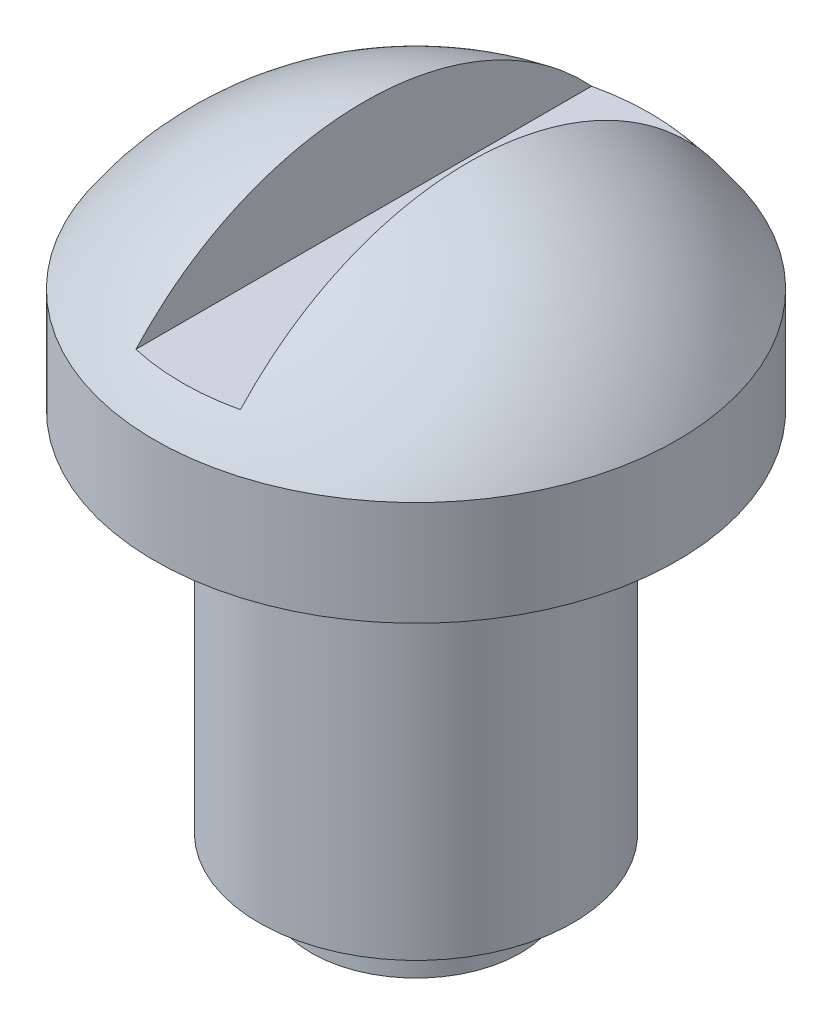
SolidWorks part; units mm, degrees
ref_plane "Front Plane" through (0, 0, 0) normal (0, 0, 1) x (1, 0, 0)
ref_plane "Top Plane" through (0, 0, 0) normal (0, 1, 0) x (1, 0, 0)
ref_plane "Right Plane" through (0, 0, 0) normal (1, 0, 0) x (0, 0, -1)
sketch "Sketch2" plane through (0, 0, 0) normal (0, 0, 1) x (1, 0, 0)
  line L0 (0, 0) -> (0, -12.6834)
  line L1 (0, -12.6834) -> (2, -12.6834)
  line L2 (2, -12.6834) -> (2, -11.6834)
  line L3 (2, -11.6834) -> (3, -11.6834)
  line L4 (3, -11.6834) -> (3, -4.6834)
  line L5 (3, -4.6834) -> (5, -4.6834)
  line L6 (5, -4.6834) -> (5, -2.6834)
  arc A0 (0, 0) -> (5, -2.6834) centre (0, -6) cw
  point P10 (0, 0)
  point P11 (0, 0)
  dimension "D6" = 6
  dimension "D1" = 2
  dimension "D2" = 3
  dimension "D3" = 7
  dimension "D4" = 2
  dimension "D5" = 1
  dimension "D7" = 5
revolve "Revolve1" add sketch "Sketch2" angle 360 about L0
sketch "Sketch3" plane through (0, 0, 0) normal (0, 0, 1) x (1, 0, 0)
  line L1 (-1, 2) -> (1, 2)
  line L2 (-1, 2) -> (-1, -2)
  line L3 (-1, -2) -> (1, -2)
  line L4 (1, 2) -> (1, -2)
  line L5 (-1, 2) -> (1, -2) construction
  line L6 (-1, -2) -> (1, 2) construction
  point P0 (0, 0)
  dimension "D1" = 2
  dimension "D2" = 2
extrude "Cut-Extrude1" cut sketch "Sketch3" against normal mid plane 10
